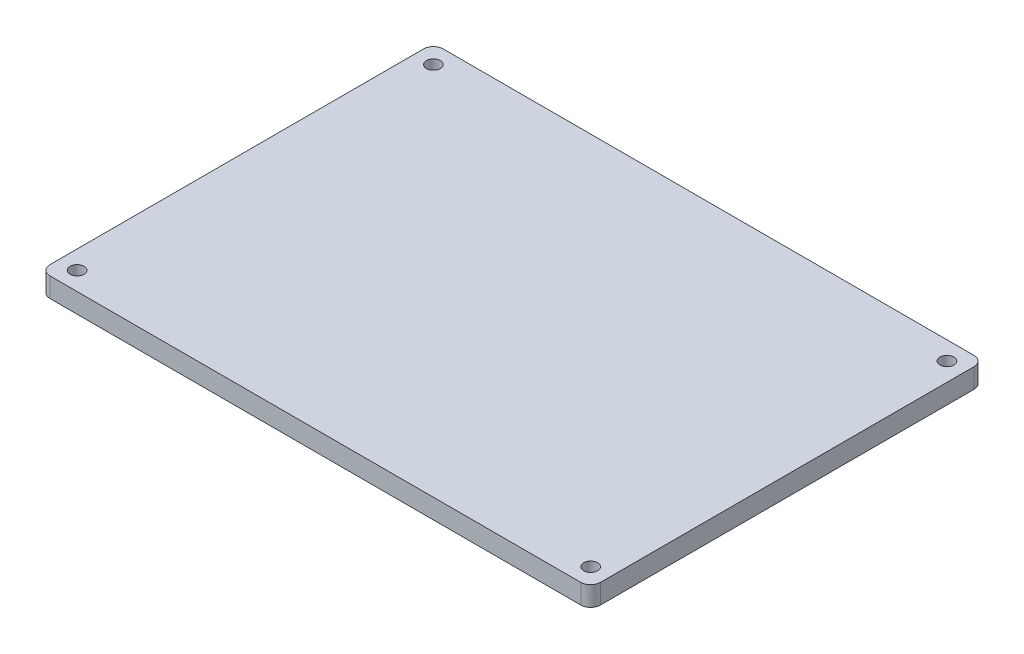
SolidWorks part; units mm, degrees
material "6061-T4 (SS)"
ref_plane "Front Plane" through (0, 0, 0) normal (0, 0, 1) x (1, 0, 0)
ref_plane "Top Plane" through (0, 0, 0) normal (0, 1, 0) x (1, 0, 0)
ref_plane "Right Plane" through (0, 0, 0) normal (1, 0, 0) x (0, 0, -1)
sketch "Sketch1" plane through (0, 670.6019, 0) normal (0, -1, 0) x (1, 0, 0)
  line L1 (-77.1716, -143.2933) -> (94.2784, -143.2933)
  line L2 (-80.3466, -146.4683) -> (-80.3466, -267.1183)
  line L3 (-77.1716, -270.2933) -> (94.2784, -270.2933)
  line L4 (97.4534, -146.4683) -> (97.4534, -267.1183)
  arc A0 (-80.3466, -267.1183) -> (-77.1716, -270.2933) centre (-77.1716, -267.1183) ccw
  arc A1 (94.2784, -270.2933) -> (97.4534, -267.1183) centre (94.2784, -267.1183) ccw
  arc A2 (94.2784, -143.2933) -> (97.4534, -146.4683) centre (94.2784, -146.4683) cw
  arc A3 (-77.1716, -143.2933) -> (-80.3466, -146.4683) centre (-77.1716, -146.4683) ccw
extrude "Boss-Extrude1" add sketch "Sketch1" along normal blind 6.35
hole_wizard "CSK for M4 Flat Head Machine Screw1" positions "Sketch3" profile "Sketch2" countersink size "M4" standard "ANSI Metric" end condition through all
sketch "Sketch3" plane through (0, 664.2519, 0) normal (0, -1, 0) x (-1, 0, 0)
  point P0 (-91.5003, 149.2464)
  point P2 (-91.5003, 264.3401)
  point P4 (74.3935, 264.3401)
  point P6 (74.3935, 149.2464)
sketch "Sketch2" plane through (91.5003, 664.2519, -149.2464) normal (1, 0, 0) x (0, 0, -1)
  line L0 (0, 0) -> (0, 6.35)
  line L1 (0, 6.35) -> (2.25, 6.35)
  line L2 (2.25, 6.35) -> (2.25, 2.45)
  line L3 (2.25, 2.45) -> (4.7, 0)
  line L5 (4.7, 0) -> (0, 0)
  line L6 (-2.25, 2.45) -> (-4.7, 0) construction
  line L11 (0, -6.35) -> (0, 107.95) construction
  dimension "Thru Hole Dia." = 4.5
  dimension "Thru Hole Depth" = 6.35
  dimension "Near C'Sink Dia." = 9.4
  dimension "Near C'Sink Angle" = 90
